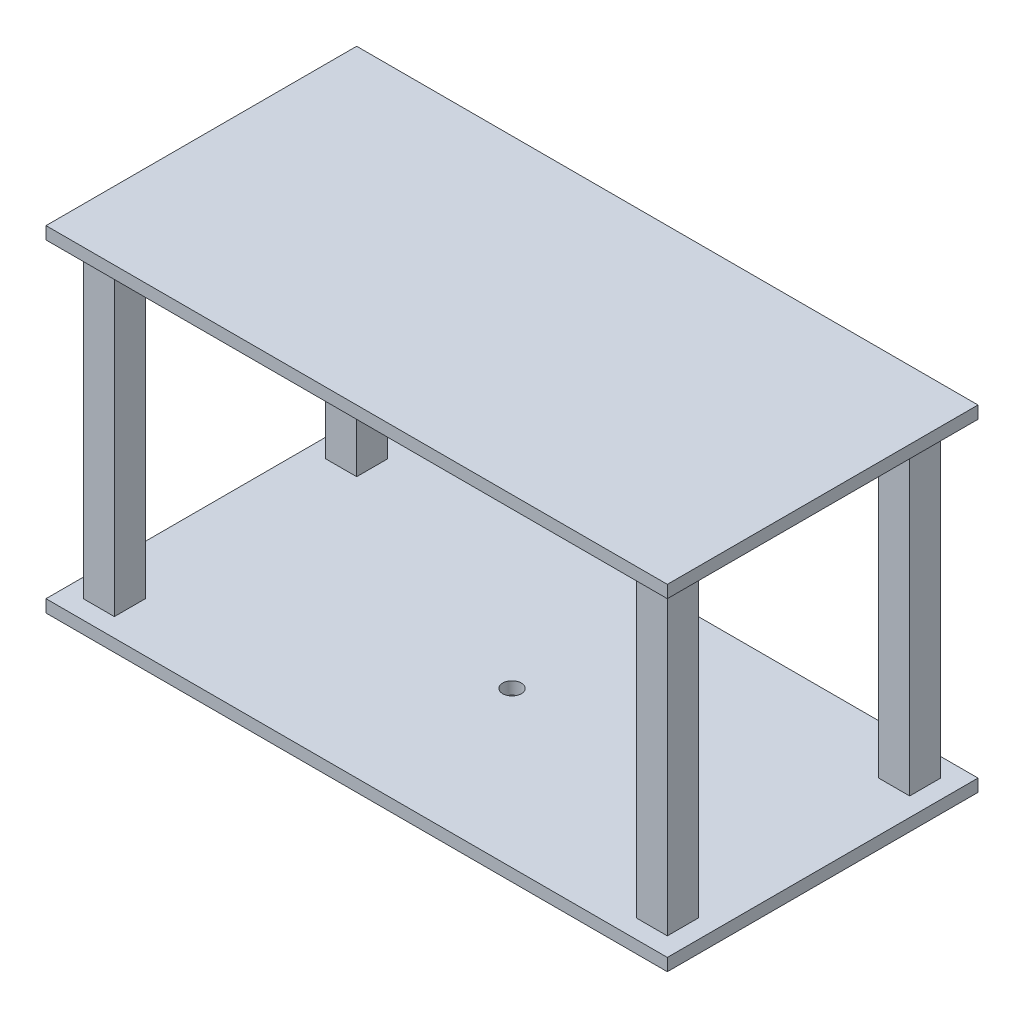
SolidWorks part; units mm, degrees
ref_plane "Front Plane" through (0, 0, 0) normal (0, 0, 1) x (1, 0, 0)
ref_plane "Top Plane" through (0, 0, 0) normal (0, 1, 0) x (1, 0, 0)
ref_plane "Right Plane" through (0, 0, 0) normal (1, 0, 0) x (0, 0, -1)
sketch "Sketch2" plane through (0, 0, 0) normal (0, 1, 0) x (1, 0, 0)
  line L0 (-50, 25) -> (50, -25) construction
  line L1 (-50, 25) -> (50, 25)
  line L2 (-50, 25) -> (-50, -25)
  line L3 (-50, -25) -> (50, -25)
  line L4 (50, 25) -> (50, -25)
  point P0 (0, 0)
  dimension "D1" = 100
  dimension "D2" = 50
extrude "Boss-Extrude1" add sketch "Sketch2" along normal blind 2
sketch "Sketch3" plane through (0, 2, 0) normal (0, 1, 0) x (1, 0, 0)
  circle A0 centre (0, 0) radius 1.5
  dimension "D1" = 3
extrude "Cut-Extrude1" cut sketch "Sketch3" against normal up to next
sketch "Sketch4" plane through (0, 2, 0) normal (0, 1, 0) x (1, 0, 0)
  line L0 (50, 25) -> (-50, 25) construction
  line L1 (-47, 22) -> (-42, 22)
  line L2 (-47, 22) -> (-47, 17)
  line L3 (-47, 17) -> (-42, 17)
  line L4 (-42, 22) -> (-42, 17)
  line L5 (-50, 25) -> (-50, -25) construction
  dimension "D1" = 5
  dimension "D2" = 3
  dimension "D3" = 3
extrude "Boss-Extrude2" add sketch "Sketch4" along normal blind 50
fillet "Fillet1" [suppressed] radius 2
mirror "Mirror1" about plane through (0, 0, 0) normal (0, 0, 1) of "Fillet1", "Boss-Extrude2" second plane through (0, 0, 0) second plane normal (1, 0, 0)
sketch "Sketch5" plane through (0, 52, 0) normal (0, 1, 0) x (1, 0, 0)
  line L1 (-50, 25) -> (50, 25)
  line L2 (-50, 25) -> (-50, -25)
  line L3 (-50, -25) -> (50, -25)
  line L4 (50, 25) -> (50, -25)
extrude "Boss-Extrude3" add sketch "Sketch5" along normal blind 2
